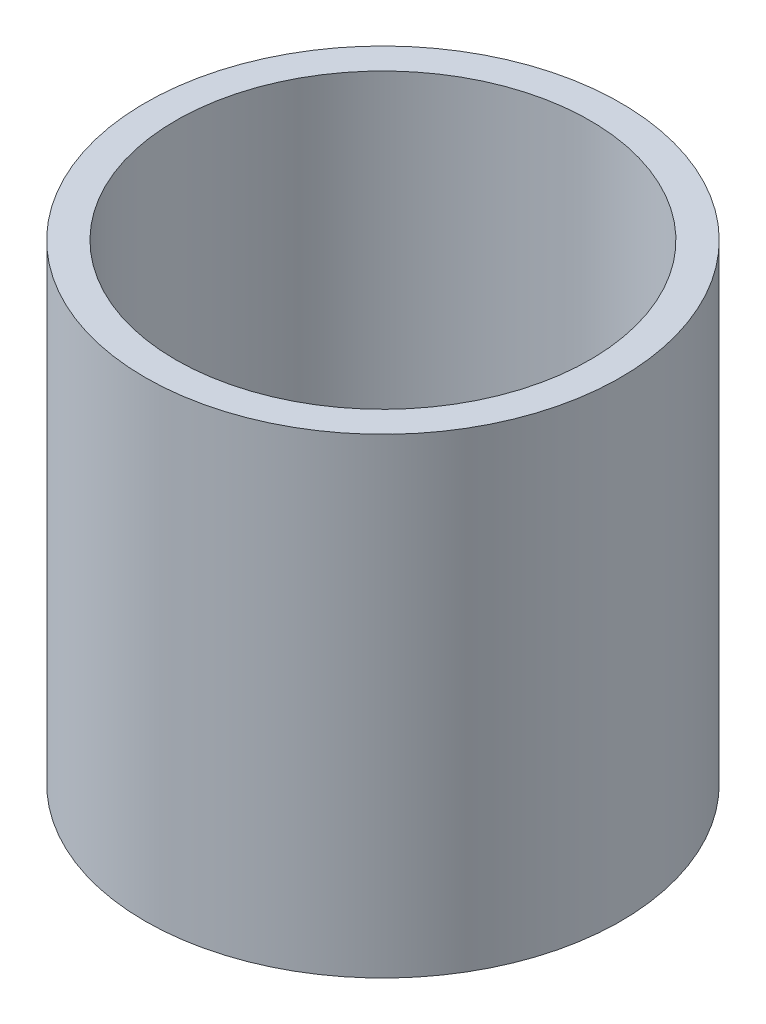
SolidWorks part; units mm, degrees
ref_plane "Front Plane" through (0, 0, 0) normal (0, 0, 1) x (1, 0, 0)
ref_plane "Top Plane" through (0, 0, 0) normal (0, 1, 0) x (1, 0, 0)
ref_plane "Right Plane" through (0, 0, 0) normal (1, 0, 0) x (0, 0, -1)
sketch "Sketch1" plane through (0, 0, 0) normal (0, 1, 0) x (1, 0, 0)
  circle A0 centre (0, 0) radius 5.588
  circle A1 centre (0, 0) radius 6.4135
  dimension "D1" = 11.176
  dimension "D2" = 12.827
extrude "Boss-Extrude1" add sketch "Sketch1" along normal mid plane 12.7
